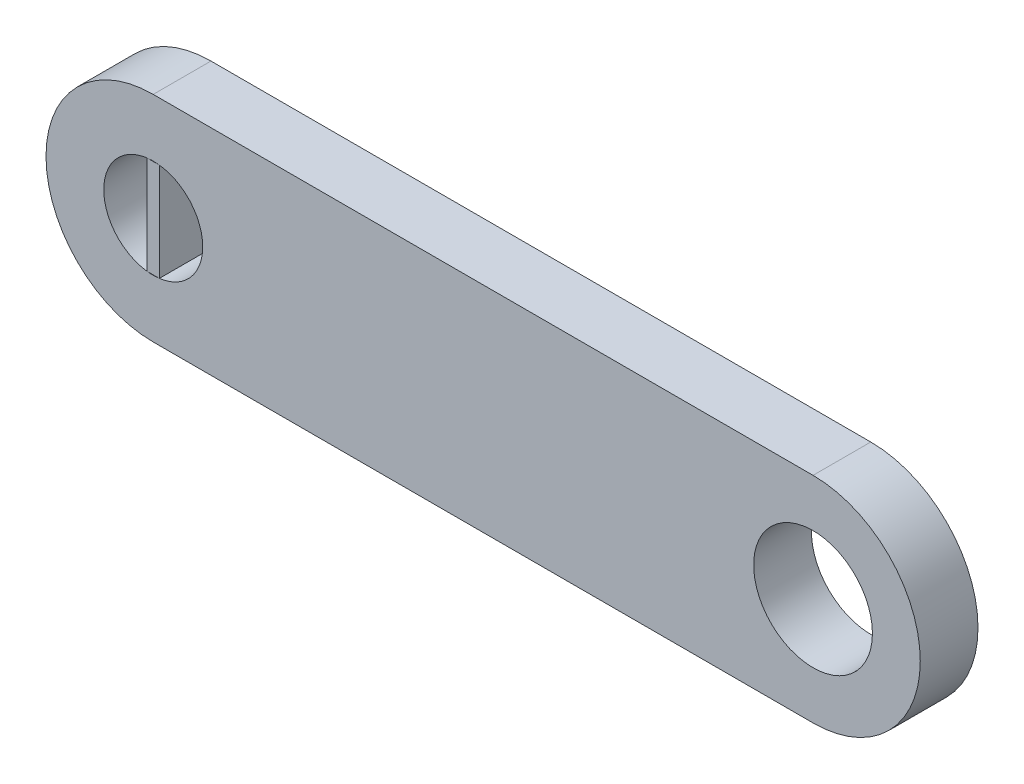
SolidWorks part; units mm, degrees
ref_plane "前视基准面" through (0, 0, 0) normal (0, 0, 1) x (1, 0, 0)
ref_plane "上视基准面" through (0, 0, 0) normal (0, 1, 0) x (1, 0, 0)
ref_plane "右视基准面" through (0, 0, 0) normal (1, 0, 0) x (0, 0, -1)
sketch "草图1" plane through (0, 0, 0) normal (0, 0, 1) x (1, 0, 0)
  line L0 (-20, 0) -> (20, 0) construction
  line L1 (-20, 6.5) -> (20, 6.5)
  line L2 (-20, -6.5) -> (20, -6.5)
  line L4 (-20.375, 2.9765) -> (-19.625, 2.9765)
  line L5 (-20.375, 2.9765) -> (-20.375, -2.9765)
  line L6 (-20.375, -2.9765) -> (-19.625, -2.9765)
  line L7 (-19.625, 2.9765) -> (-19.625, -2.9765)
  line L8 (-20.375, 2.9765) -> (-19.625, -2.9765) construction
  line L9 (-20.375, -2.9765) -> (-19.625, 2.9765) construction
  arc A0 (-20, 6.5) -> (-20, -6.5) centre (-20, 0) ccw
  arc A1 (20, -6.5) -> (20, 6.5) centre (20, 0) ccw
  circle A2 centre (-20, 0) radius 3
  circle A3 centre (20, 0) radius 3.6
  point P2 (0, 0)
  dimension "D2" = 6.5
  dimension "D3" = 6
  dimension "D4" = 7.2
  dimension "D1" = 40
  dimension "D5" = 0.75
extrude "凸台-拉伸3" add sketch "草图1" along normal blind 3.5 contours L2 A1 L1 A0 A3 A2 | L5 L6 L7 L4
